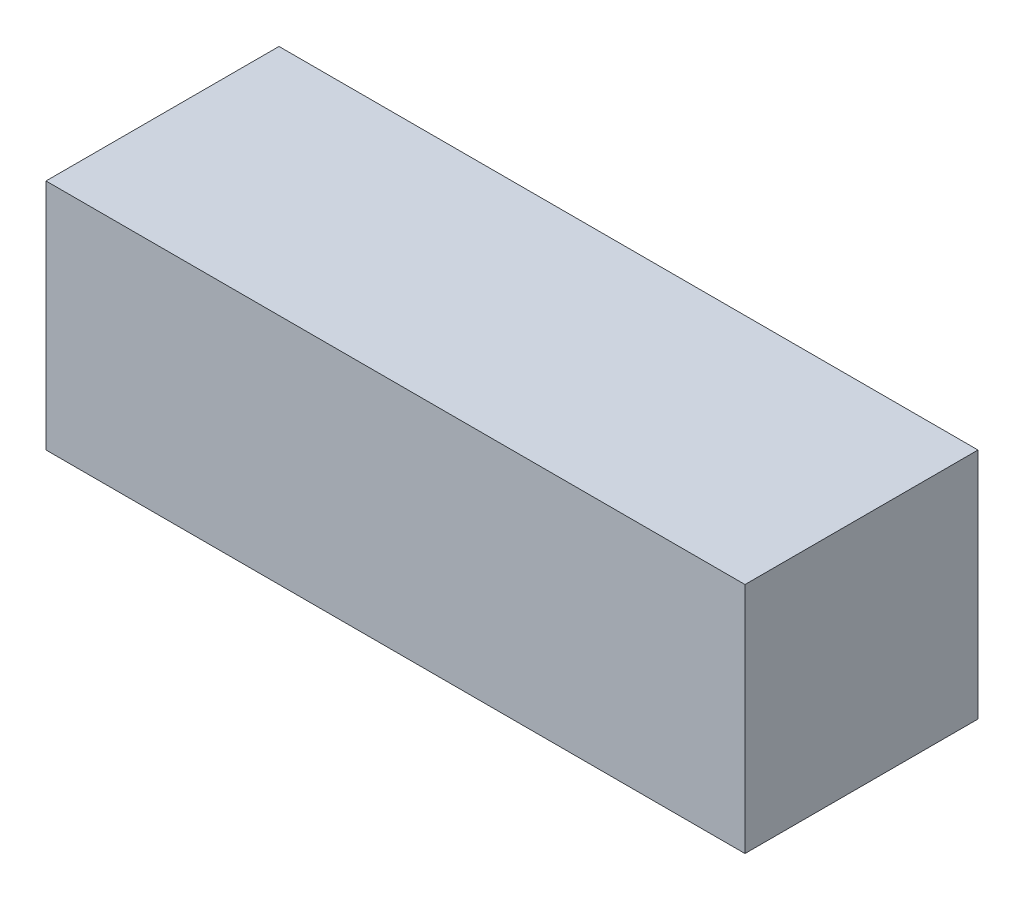
SolidWorks part; units mm, degrees
material "Plain Carbon Steel"
ref_plane "Front Plane" through (0, 0, 0) normal (0, 0, 1) x (1, 0, 0)
ref_plane "Top Plane" through (0, 0, 0) normal (0, 1, 0) x (1, 0, 0)
ref_plane "Right Plane" through (0, 0, 0) normal (1, 0, 0) x (0, 0, -1)
sketch "Sketch1" plane through (0, 0, 0) normal (0, 1, 0) x (1, 0, 0)
  line L1 (0, 0) -> (30, 0)
  line L2 (0, 0) -> (0, 10)
  line L3 (0, 10) -> (30, 10)
  line L4 (30, 0) -> (30, 10)
  dimension "D1" = 10
  dimension "D2" = 30
extrude "Boss-Extrude1" add sketch "Sketch1" along normal blind 10
